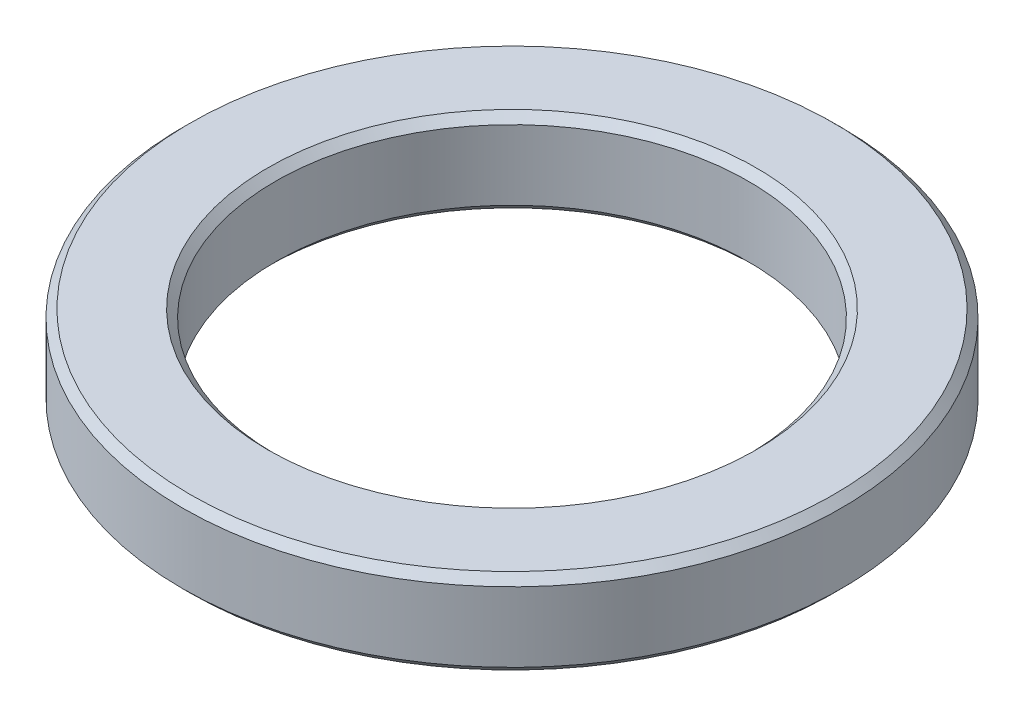
SolidWorks part; units mm, degrees
ref_plane "Front Plane" through (0, 0, 0) normal (0, 0, 1) x (1, 0, 0)
ref_plane "Top Plane" through (0, 0, 0) normal (0, 1, 0) x (1, 0, 0)
ref_plane "Right Plane" through (0, 0, 0) normal (1, 0, 0) x (0, 0, -1)
sketch "Sketch1" plane through (0, 0, 0) normal (0, 1, 0) x (1, 0, 0)
  circle A0 centre (0, 0) radius 3.05
  circle A1 centre (0, 0) radius 4.25
  dimension "D1" = 6.1
  dimension "D2" = 8.5
extrude "Boss-Extrude1" add sketch "Sketch1" along normal blind 1.1
chamfer "Chamfer1" distance 0.1 angle 45 4 edges at (0, 0, 3.05) (0, 0, 4.25) (0, 1.1, 3.05) (0, 1.1, 4.25)
